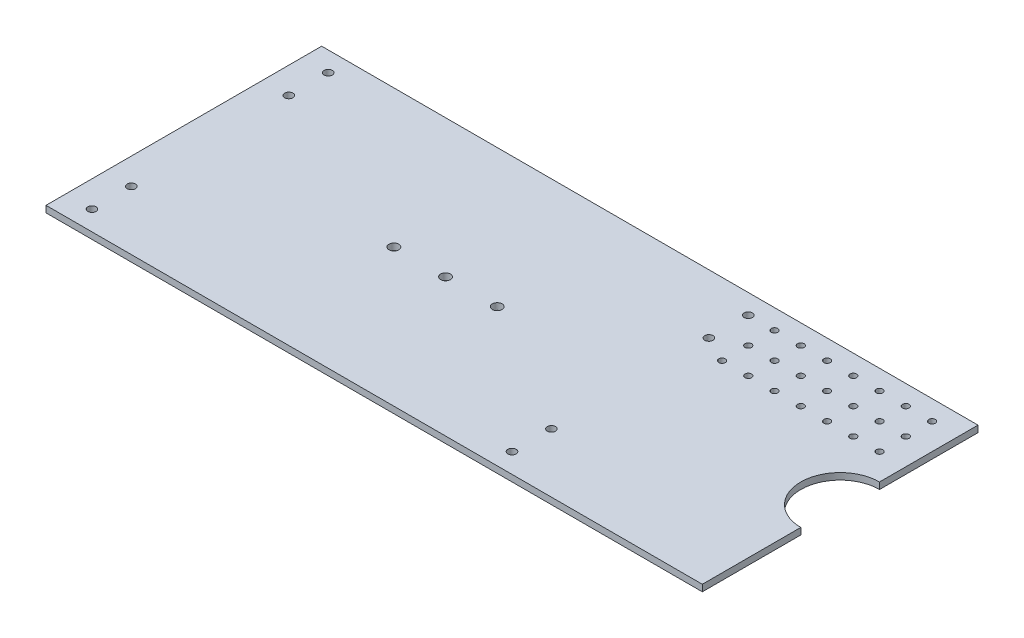
SolidWorks part; units mm, degrees
ref_plane "Front Plane" through (0, 0, 0) normal (0, 0, 1) x (1, 0, 0)
ref_plane "Top Plane" through (0, 0, 0) normal (0, 1, 0) x (1, 0, 0)
ref_plane "Right Plane" through (0, 0, 0) normal (1, 0, 0) x (0, 0, -1)
sketch "Sketch1" plane through (0, 0, 0) normal (0, 1, 0) x (1, 0, 0)
  line L1 (-317.5, -133.35) -> (317.5, -133.35)
  line L2 (-317.5, -133.35) -> (-317.5, 133.35)
  line L3 (-317.5, 133.35) -> (317.5, 133.35)
  line L4 (317.5, -133.35) -> (317.5, 133.35)
  line L5 (-317.5, -133.35) -> (317.5, 133.35) construction
  line L6 (-317.5, 133.35) -> (317.5, -133.35) construction
  point P0 (0, 0)
  dimension "D1" = 266.7
  dimension "D2" = 635
extrude "Boss-Extrude1" add sketch "Sketch1" along normal blind 6.35
sketch "Sketch2" plane through (0, 0, 0) normal (0, 1, 0) x (-1, 0, 0)
  line L1 (-317.5, 0) -> (317.5, 0) construction
  line L3 (55, 0) -> (-55, 0) construction
  line L4 (-317.5, 133.35) -> (-317.5, -133.35) construction
  line L5 (317.5, -133.35) -> (317.5, 133.35) construction
  circle A0 centre (114.3, 0) radius 4.7625
  circle A1 centre (64.3, 0) radius 4.7625
  circle A2 centre (14.3, 0) radius 4.7625
  dimension "D1" = 9.525
  dimension "D3" = 50
  dimension "D2" = 203.2
  dimension "D4" = 50
extrude "Cut-Extrude2" cut sketch "Sketch2" against normal through all and the other way through all
sketch "Sketch3" plane through (0, 0, 0) normal (0, 1, 0) x (1, 0, 0)
  line L0 (317.5, 133.35) -> (-317.5, 133.35) construction
  line L1 (-317.5, 133.35) -> (-317.5, -133.35) construction
  line L2 (-317.5, -133.35) -> (317.5, -133.35) construction
  circle A0 centre (-292.1, 114.3) radius 3.9688
  circle A1 centre (-292.1, 76.2) radius 3.9688
  circle A2 centre (-292.1, -76.2) radius 3.9688
  circle A3 centre (-292.1, -114.3) radius 3.9688
  circle A4 centre (114.3, 114.3) radius 3.9687
  circle A5 centre (114.3, 76.2) radius 3.9687
  circle A6 centre (114.3, -76.2) radius 3.9687
  circle A7 centre (114.3, -114.3) radius 3.9687
  dimension "D6" = 7.9375
  dimension "D1" = 19.05
  dimension "D2" = 38.1
  dimension "D3" = 25.4
  dimension "D4" = 38.1
  dimension "D5" = 19.05
  dimension "D7" = 406.4
extrude "Cut-Extrude4" cut sketch "Sketch3" along normal through all
sketch "Sketch4" plane through (0, 0, 0) normal (0, 1, 0) x (1, 0, 0)
  line L0 (317.5, -133.35) -> (317.5, 133.35) construction
  circle A0 centre (317.5, 0) radius 38.1
  dimension "D1" = 76.2
extrude "Cut-Extrude6" cut sketch "Sketch4" along normal through all
sketch "Sketch5" plane through (0, 6.35, 0) normal (0, 1, 0) x (1, 0, 0)
  line L0 (317.5, 133.35) -> (-317.5, 133.35) construction
  circle A0 centre (139.7, 114.3) radius 3.175
  circle A1 centre (114.3, 114.3) radius 3.9687 construction
  circle A2 centre (165.1, 114.3) radius 3.175
  circle A3 centre (190.5, 114.3) radius 3.175
  circle A5 centre (215.9, 114.3) radius 3.175
  circle A6 centre (241.3, 114.3) radius 3.175
  circle A7 centre (266.7, 114.3) radius 3.175
  circle A8 centre (292.1, 114.3) radius 3.175
  circle A11 centre (165.1, 88.9) radius 3.175
  circle A12 centre (190.5, 88.9) radius 3.175
  circle A13 centre (215.9, 88.9) radius 3.175
  circle A14 centre (241.3, 88.9) radius 3.175
  circle A15 centre (266.7, 88.9) radius 3.175
  circle A16 centre (292.1, 88.9) radius 3.175
  circle A19 centre (165.1, 63.5) radius 3.175
  circle A20 centre (190.5, 63.5) radius 3.175
  circle A21 centre (215.9, 63.5) radius 3.175
  circle A22 centre (241.3, 63.5) radius 3.175
  circle A23 centre (266.7, 63.5) radius 3.175
  circle A24 centre (292.1, 63.5) radius 3.175
  circle A27 centre (139.7, 88.9) radius 3.175
  circle A28 centre (139.7, 63.5) radius 3.175
  dimension "D1" = 6.35
  dimension "D2" = 25.4
  dimension "D6" = 25.4
  dimension "D7" = 25.4
  dimension "D3" = 7
  dimension "D4" = 19.05
  dimension "D5" = 3
extrude "Cut-Extrude7" cut sketch "Sketch5" against normal through all
